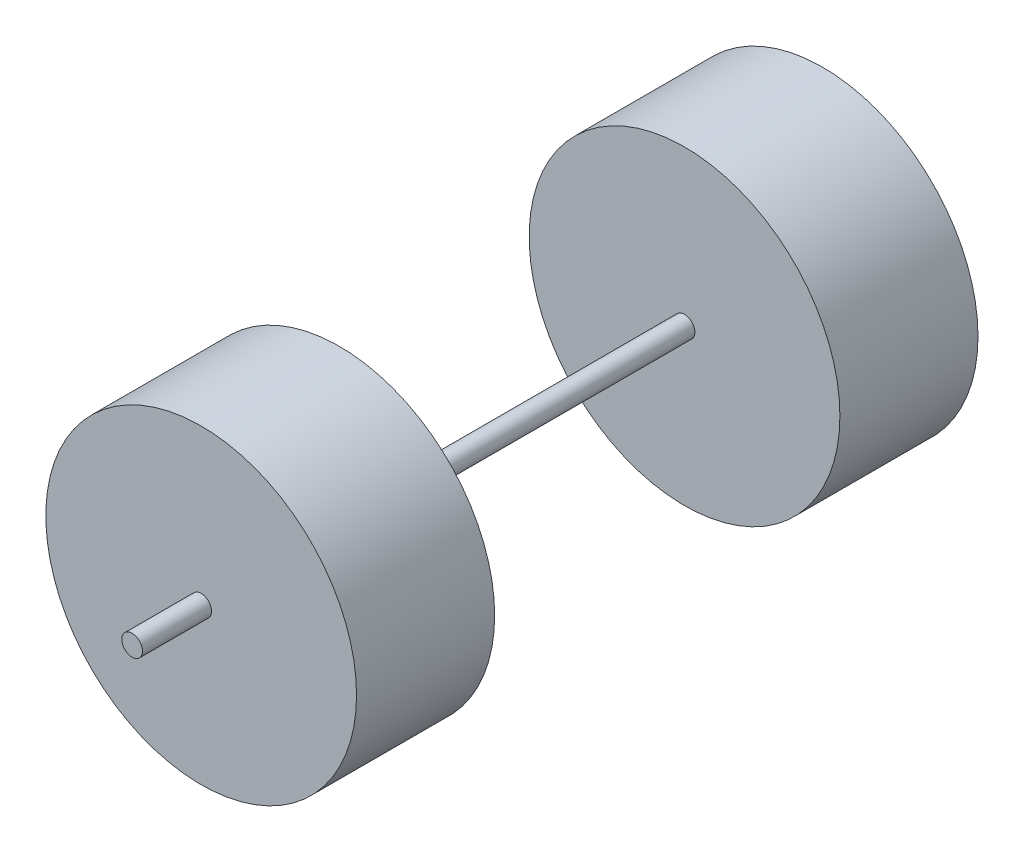
SolidWorks part; units mm, degrees
ref_plane "Plano frontal" through (0, 0, 0) normal (0, 0, 1) x (1, 0, 0)
ref_plane "Plano superior" through (0, 0, 0) normal (0, 1, 0) x (1, 0, 0)
ref_plane "Plano direito" through (0, 0, 0) normal (1, 0, 0) x (0, 0, -1)
sketch "Esboço1" plane through (0, 0, 0) normal (0, 0, 1) x (1, 0, 0)
  circle A1 centre (0, 0) radius 22.5
  dimension "D1" = 45
extrude "Ressalto-extrusão3" add sketch "Esboço1" along normal blind 20
sketch "Esboço3" plane through (0, 0, 20) normal (0, 0, 1) x (1, 0, 0)
  circle A0 centre (0, 0) radius 1.5
extrude "Ressalto-extrusão4" add sketch "Esboço3" along normal blind 50
sketch "Esboço4" plane through (0, 0, 70) normal (0, 0, 1) x (1, 0, 0)
  circle A0 centre (0, 0) radius 22.5
extrude "Ressalto-extrusão5" add sketch "Esboço4" along normal blind 20
sketch "Esboço5" plane through (0, 0, 90) normal (0, 0, 1) x (1, 0, 0)
  circle A0 centre (0, 0) radius 1.5
extrude "Ressalto-extrusão6" add sketch "Esboço5" along normal blind 10
sketch "Esboço6" plane through (0, 0, 0) normal (0, 0, -1) x (-1, 0, 0)
  circle A0 centre (0, 0) radius 1.5
extrude "Ressalto-extrusão7" add sketch "Esboço6" along normal blind 10
